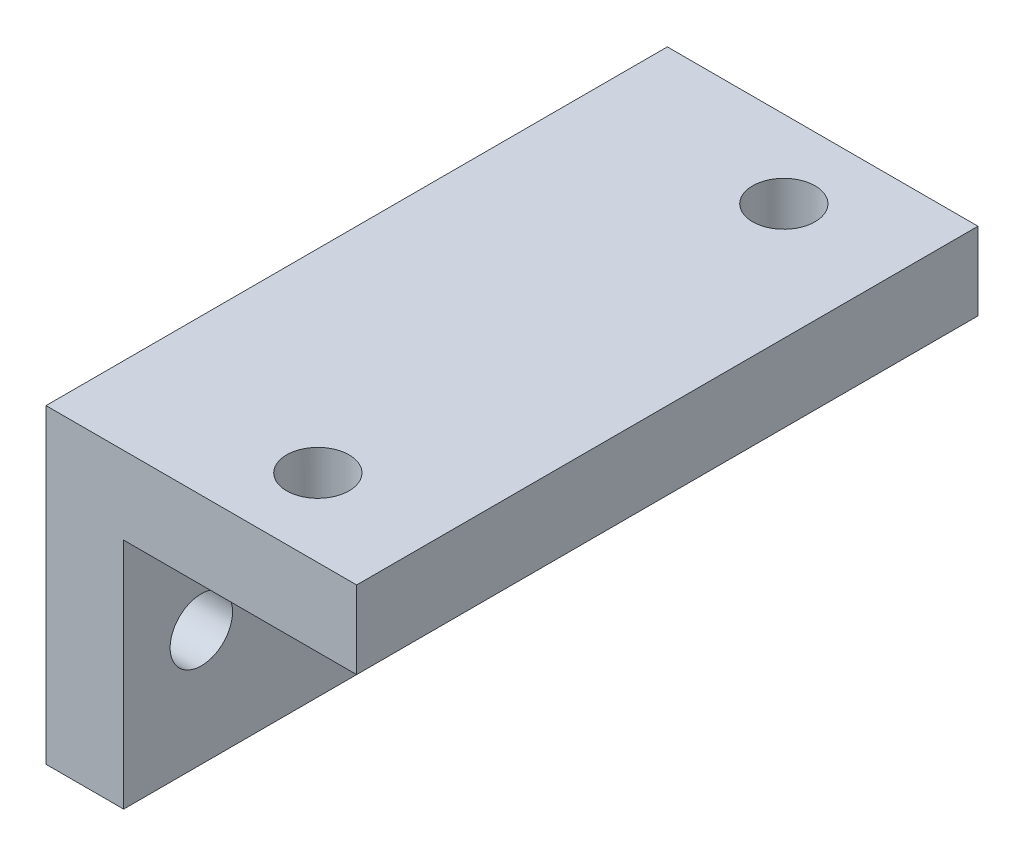
SolidWorks part; units mm, degrees
material "6061-T6 (SS)"
ref_plane "Front Plane" through (0, 0, 0) normal (0, 0, 1) x (1, 0, 0)
ref_plane "Top Plane" through (0, 0, 0) normal (0, 1, 0) x (1, 0, 0)
ref_plane "Right Plane" through (0, 0, 0) normal (1, 0, 0) x (0, 0, -1)
sketch "Sketch1" plane through (0, 0, 0) normal (0, 0, 1) x (1, 0, 0)
  line L0 (0, 0) -> (19.05, 0)
  line L1 (19.05, 0) -> (19.05, 6.35)
  line L2 (19.05, 6.35) -> (-6.35, 6.35)
  line L3 (-6.35, 6.35) -> (-6.35, -19.05)
  line L4 (-6.35, -19.05) -> (0, -19.05)
  line L5 (0, -19.05) -> (0, 0)
  dimension "D1" = 6.35
  dimension "D2" = 25.4
extrude "Boss-Extrude1" add sketch "Sketch1" along normal mid plane 50.8
hole_wizard "#10 Clearance Hole1" positions "Sketch3" profile "Sketch2" hole size "#10" standard "ANSI Inch" end condition up to next
sketch "Sketch3" plane through (0, 0, 0) normal (0, -1, 0) x (-1, 0, 0)
  line L0 (-9.525, 25.4) -> (-9.525, 50025.4) construction
  line L1 (0, 25.4) -> (-19.05, 25.4) construction
  line L2 (-19.05, 0) -> (-50019.05, 0) construction
  line L3 (-19.05, -25.4) -> (-19.05, 25.4) construction
  point P0 (-9.525, -19.05)
  point P2 (-9.525, 19.05)
  point P9 (-9.525, 25.4)
  point P14 (-19.05, 0)
  dimension "D1" = 38.1
sketch "Sketch2" plane through (9.525, 0, 19.05) normal (1, 0, 0) x (0, 0, -1)
  line L0 (0, 0) -> (0, 6.35)
  line L1 (0, 6.35) -> (2.5527, 6.35)
  line L2 (2.5527, 6.35) -> (2.5527, 0)
  line L5 (2.5527, 0) -> (0, 0)
  line L11 (0, -6.35) -> (0, 107.95) construction
  dimension "Thru Hole Dia." = 5.1054
  dimension "Thru Hole Depth" = 6.35
hole_wizard "#10 Clearance Hole2" positions "Sketch5" profile "Sketch4" hole size "#10" standard "ANSI Inch"
sketch "Sketch5" plane through (0, 0, 0) normal (1, 0, 0) x (0, 0, -1)
  line L0 (-25.4, -9.525) -> (-50025.4, -9.525) construction
  line L1 (-25.4, -19.05) -> (-25.4, 0) construction
  line L2 (0, -19.05) -> (0, 49980.95) construction
  line L3 (-25.4, -19.05) -> (25.4, -19.05) construction
  point P0 (19.05, -9.525)
  point P2 (-19.05, -9.525)
  point P9 (-25.4, -9.525)
  point P14 (0, -19.05)
  dimension "D1" = 38.1
sketch "Sketch4" plane through (0, -9.525, -19.05) normal (0, 1, 0) x (0, 0, -1)
  line L0 (0, 0) -> (0, 7.8838)
  line L1 (0, 7.8838) -> (2.5527, 6.35)
  line L2 (2.5527, 6.35) -> (2.5527, 0)
  line L5 (2.5527, 0) -> (0, 0)
  line L10 (0, 7.8838) -> (-2.5527, 6.35) construction
  line L11 (0, -6.35) -> (0, 107.95) construction
  dimension "Hole Dia." = 5.1054
  dimension "Hole Depth" = 6.35
  dimension "Drill Angle" = 118
